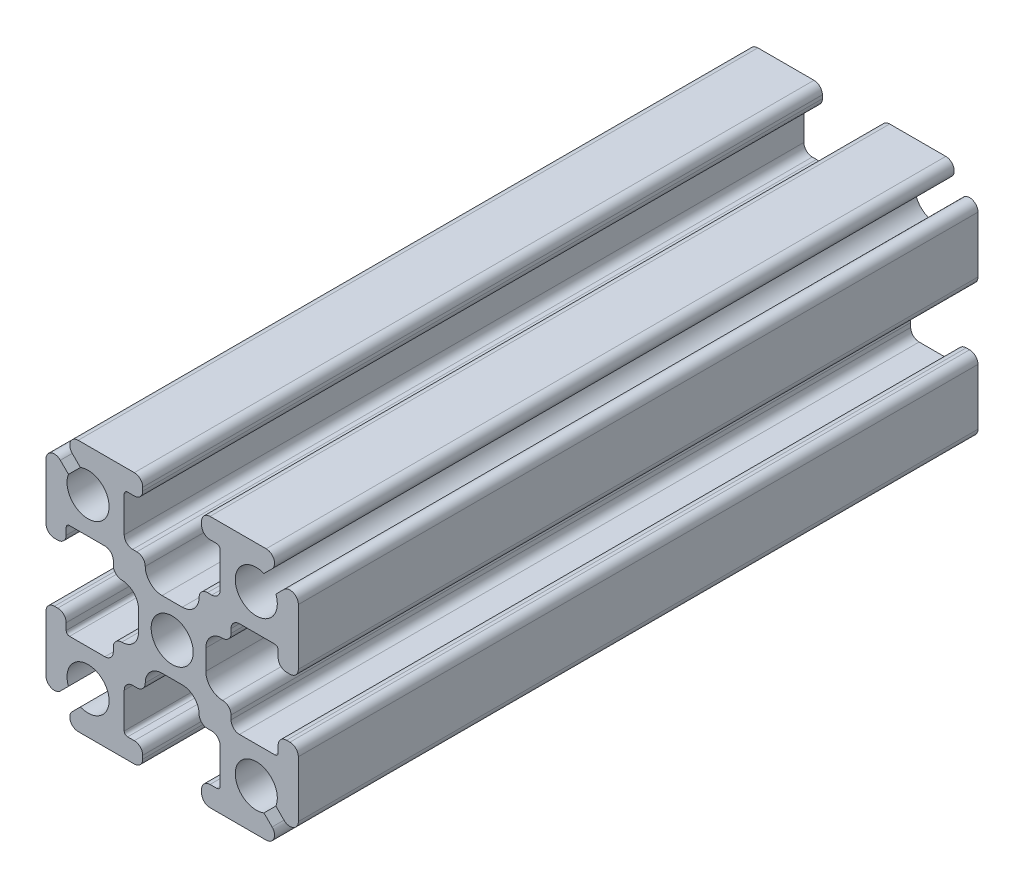
SolidWorks part; units mm, degrees
ref_plane "Front" through (0, 0, 0) normal (0, 0, 1) x (1, 0, 0)
ref_plane "Top" through (0, 0, 0) normal (0, 1, 0) x (1, 0, 0)
ref_plane "Right" through (0, 0, 0) normal (1, 0, 0) x (0, 0, -1)
sketch "Sketch1" plane through (0, 0, 0) normal (0, 0, 1) x (1, 0, 0)
  line L0 (6.6464, 5.9393) -> (6.1636, 5.4565)
  line L1 (5.4565, 6.1636) -> (5.9393, 6.6464)
  line L2 (5.5858, 7.5) -> (2.25, 7.5)
  line L3 (1.75, 7) -> (1.75, 6.8)
  line L4 (2.25, 6.3) -> (2.65, 6.3)
  line L5 (2.85, 6.1) -> (2.85, 4)
  line L6 (2.35, 3.5) -> (2.1, 3.5)
  line L7 (0.6, 2) -> (-0.6, 2)
  line L8 (-2.1, 3.5) -> (-2.35, 3.5)
  line L9 (-2.85, 4) -> (-2.85, 6.1)
  line L10 (-2.65, 6.3) -> (-2.25, 6.3)
  line L11 (-1.75, 6.8) -> (-1.75, 7)
  line L12 (-2.25, 7.5) -> (-5.5858, 7.5)
  line L13 (-5.9393, 6.6464) -> (-5.4565, 6.1636)
  line L14 (-6.1636, 5.4565) -> (-6.6464, 5.9393)
  line L15 (-7.5, 5.5858) -> (-7.5, 2.25)
  line L16 (-7, 1.75) -> (-6.8, 1.75)
  line L17 (-6.3, 2.25) -> (-6.3, 2.65)
  line L18 (-6.1, 2.85) -> (-4, 2.85)
  line L19 (-3.5, 2.35) -> (-3.5, 2.1)
  line L20 (-2, 0.6) -> (-2, -0.6)
  line L21 (-3.5, -2.1) -> (-3.5, -2.35)
  line L22 (-4, -2.85) -> (-6.1, -2.85)
  line L23 (-6.3, -2.65) -> (-6.3, -2.25)
  line L24 (-6.8, -1.75) -> (-7, -1.75)
  line L25 (-7.5, -2.25) -> (-7.5, -5.5858)
  line L26 (-6.6464, -5.9393) -> (-6.1636, -5.4565)
  line L27 (-5.4565, -6.1636) -> (-5.9393, -6.6464)
  line L28 (-5.5858, -7.5) -> (-2.25, -7.5)
  line L29 (-1.75, -7) -> (-1.75, -6.8)
  line L30 (-2.25, -6.3) -> (-2.65, -6.3)
  line L31 (-2.85, -6.1) -> (-2.85, -4)
  line L32 (-2.35, -3.5) -> (-2.1, -3.5)
  line L33 (-0.6, -2) -> (0.6, -2)
  line L34 (2.1, -3.5) -> (2.35, -3.5)
  line L35 (2.85, -4) -> (2.85, -6.1)
  line L36 (2.65, -6.3) -> (2.25, -6.3)
  line L37 (1.75, -6.8) -> (1.75, -7)
  line L38 (2.25, -7.5) -> (5.5858, -7.5)
  line L39 (5.9393, -6.6464) -> (5.4565, -6.1636)
  line L40 (6.1636, -5.4565) -> (6.6464, -5.9393)
  line L41 (7.5, -5.5858) -> (7.5, -2.25)
  line L42 (7, -1.75) -> (6.8, -1.75)
  line L43 (6.3, -2.25) -> (6.3, -2.65)
  line L44 (6.1, -2.85) -> (4, -2.85)
  line L45 (3.5, -2.35) -> (3.5, -2.1)
  line L46 (2, -0.6) -> (2, 0.6)
  line L47 (3.5, 2.1) -> (3.5, 2.35)
  line L48 (4, 2.85) -> (6.1, 2.85)
  line L49 (6.3, 2.65) -> (6.3, 2.25)
  line L50 (6.8, 1.75) -> (7, 1.75)
  line L51 (7.5, 2.25) -> (7.5, 5.5858)
  circle A0 centre (0, 0) radius 1.25
  arc A1 (6.1636, 5.4565) -> (5.4565, 6.1636) centre (5, 5) cw
  arc A2 (5.9393, 6.6464) -> (5.5858, 7.5) centre (5.5858, 7) ccw
  arc A3 (2.25, 7.5) -> (1.75, 7) centre (2.25, 7) ccw
  arc A4 (1.75, 6.8) -> (2.25, 6.3) centre (2.25, 6.8) ccw
  arc A5 (2.65, 6.3) -> (2.85, 6.1) centre (2.65, 6.1) cw
  arc A6 (2.85, 4) -> (2.35, 3.5) centre (2.35, 4) cw
  arc A7 (2.1, 3.5) -> (1.6, 3) centre (2.1, 3) ccw
  arc A8 (1.6, 3) -> (0.6, 2) centre (0.6, 3) cw
  arc A9 (-0.6, 2) -> (-1.6, 3) centre (-0.6, 3) cw
  arc A10 (-1.6, 3) -> (-2.1, 3.5) centre (-2.1, 3) ccw
  arc A11 (-2.35, 3.5) -> (-2.85, 4) centre (-2.35, 4) cw
  arc A12 (-2.85, 6.1) -> (-2.65, 6.3) centre (-2.65, 6.1) cw
  arc A13 (-2.25, 6.3) -> (-1.75, 6.8) centre (-2.25, 6.8) ccw
  arc A14 (-1.75, 7) -> (-2.25, 7.5) centre (-2.25, 7) ccw
  arc A15 (-5.5858, 7.5) -> (-5.9393, 6.6464) centre (-5.5858, 7) ccw
  arc A16 (-5.4565, 6.1636) -> (-6.1636, 5.4565) centre (-5, 5) cw
  arc A17 (-6.6464, 5.9393) -> (-7.5, 5.5858) centre (-7, 5.5858) ccw
  arc A18 (-7.5, 2.25) -> (-7, 1.75) centre (-7, 2.25) ccw
  arc A19 (-6.8, 1.75) -> (-6.3, 2.25) centre (-6.8, 2.25) ccw
  arc A20 (-6.3, 2.65) -> (-6.1, 2.85) centre (-6.1, 2.65) cw
  arc A21 (-4, 2.85) -> (-3.5, 2.35) centre (-4, 2.35) cw
  arc A22 (-3.5, 2.1) -> (-3, 1.6) centre (-3, 2.1) ccw
  arc A23 (-3, 1.6) -> (-2, 0.6) centre (-3, 0.6) cw
  arc A24 (-2, -0.6) -> (-3, -1.6) centre (-3, -0.6) cw
  arc A25 (-3, -1.6) -> (-3.5, -2.1) centre (-3, -2.1) ccw
  arc A26 (-3.5, -2.35) -> (-4, -2.85) centre (-4, -2.35) cw
  arc A27 (-6.1, -2.85) -> (-6.3, -2.65) centre (-6.1, -2.65) cw
  arc A28 (-6.3, -2.25) -> (-6.8, -1.75) centre (-6.8, -2.25) ccw
  arc A29 (-7, -1.75) -> (-7.5, -2.25) centre (-7, -2.25) ccw
  arc A30 (-7.5, -5.5858) -> (-6.6464, -5.9393) centre (-7, -5.5858) ccw
  arc A31 (-6.1636, -5.4565) -> (-5.4565, -6.1636) centre (-5, -5) cw
  arc A32 (-5.9393, -6.6464) -> (-5.5858, -7.5) centre (-5.5858, -7) ccw
  arc A33 (-2.25, -7.5) -> (-1.75, -7) centre (-2.25, -7) ccw
  arc A34 (-1.75, -6.8) -> (-2.25, -6.3) centre (-2.25, -6.8) ccw
  arc A35 (-2.65, -6.3) -> (-2.85, -6.1) centre (-2.65, -6.1) cw
  arc A36 (-2.85, -4) -> (-2.35, -3.5) centre (-2.35, -4) cw
  arc A37 (-2.1, -3.5) -> (-1.6, -3) centre (-2.1, -3) ccw
  arc A38 (-1.6, -3) -> (-0.6, -2) centre (-0.6, -3) cw
  arc A39 (0.6, -2) -> (1.6, -3) centre (0.6, -3) cw
  arc A40 (1.6, -3) -> (2.1, -3.5) centre (2.1, -3) ccw
  arc A41 (2.35, -3.5) -> (2.85, -4) centre (2.35, -4) cw
  arc A42 (2.85, -6.1) -> (2.65, -6.3) centre (2.65, -6.1) cw
  arc A43 (2.25, -6.3) -> (1.75, -6.8) centre (2.25, -6.8) ccw
  arc A44 (1.75, -7) -> (2.25, -7.5) centre (2.25, -7) ccw
  arc A45 (5.5858, -7.5) -> (5.9393, -6.6464) centre (5.5858, -7) ccw
  arc A46 (5.4565, -6.1636) -> (6.1636, -5.4565) centre (5, -5) cw
  arc A47 (6.6464, -5.9393) -> (7.5, -5.5858) centre (7, -5.5858) ccw
  arc A48 (7.5, -2.25) -> (7, -1.75) centre (7, -2.25) ccw
  arc A49 (6.8, -1.75) -> (6.3, -2.25) centre (6.8, -2.25) ccw
  arc A50 (6.3, -2.65) -> (6.1, -2.85) centre (6.1, -2.65) cw
  arc A51 (4, -2.85) -> (3.5, -2.35) centre (4, -2.35) cw
  arc A52 (3.5, -2.1) -> (3, -1.6) centre (3, -2.1) ccw
  arc A53 (3, -1.6) -> (2, -0.6) centre (3, -0.6) cw
  arc A54 (2, 0.6) -> (3, 1.6) centre (3, 0.6) cw
  arc A55 (3, 1.6) -> (3.5, 2.1) centre (3, 2.1) ccw
  arc A56 (3.5, 2.35) -> (4, 2.85) centre (4, 2.35) cw
  arc A57 (6.1, 2.85) -> (6.3, 2.65) centre (6.1, 2.65) cw
  arc A58 (6.3, 2.25) -> (6.8, 1.75) centre (6.8, 2.25) ccw
  arc A59 (7, 1.75) -> (7.5, 2.25) centre (7, 2.25) ccw
  arc A60 (7.5, 5.5858) -> (6.6464, 5.9393) centre (7, 5.5858) ccw
extrude "Boss-Extrude1" add sketch "Sketch1" along normal blind 40.4
